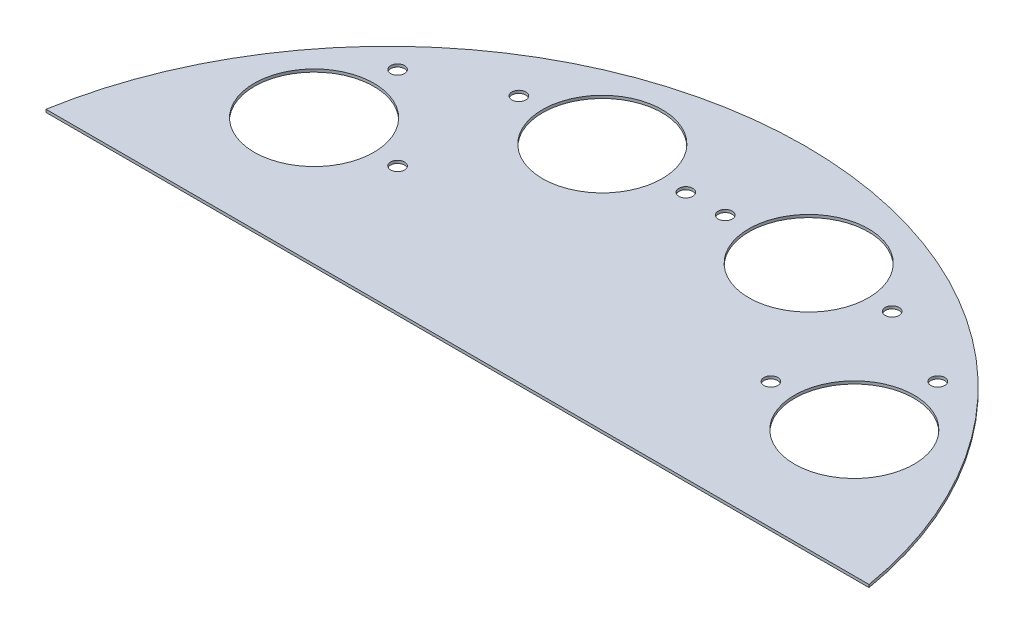
SolidWorks part; units mm, degrees
material "1060 Alloy"
ref_plane "Front Plane" through (0, 0, 0) normal (0, 0, 1) x (1, 0, 0)
ref_plane "Top Plane" through (0, 0, 0) normal (0, 1, 0) x (1, 0, 0)
ref_plane "Right Plane" through (0, 0, 0) normal (1, 0, 0) x (0, 0, -1)
sketch "Sketch3" plane through (0, 0, 0) normal (0, 1, 0) x (1, 0, 0)
  line L5 (-149.8445, -43.9726) -> (150.1555, -43.9726) construction
  line L6 (97.2375, 26.5616) -> (0.1555, -43.9726)
  line L7 (-86.3026, -18.9726) -> (-147.7465, -18.9726)
  line L9 (86.6136, -18.9726) -> (148.0575, -18.9726)
  line L11 (86.6136, -18.9726) -> (-86.3026, -18.9726)
  circle A10 centre (0.1555, -43.9726) radius 120 construction
  circle A11 centre (0.1555, -43.9726) radius 90 construction
  circle A12 centre (0.1555, -43.9726) radius 150
  circle A13 centre (97.2375, 26.5616) radius 21.5
  circle A14 centre (37.2375, 70.1542) radius 21.5
  circle A15 centre (-36.9265, 70.1542) radius 21.5
  circle A16 centre (-96.9265, 26.5616) radius 21.5
  point P5 (0.1555, -43.9726)
  point P9 (0.1555, -43.9726)
  point P22 (0.1555, -43.9726)
  dimension "D3" = 300
  dimension "D7" = 43
  dimension "D4" = 36
  dimension "D5" = 4
  dimension "D2" = 240
  dimension "D1" = 180
extrude "Boss-Extrude3" add sketch "Sketch3" along normal blind 1
sketch "Sketch5" plane through (0, 1, 0) normal (0, 1, 0) x (1, 0, 0)
  line L0 (37.2375, 70.1542) -> (-36.9265, 70.1542) construction
  line L1 (-36.9265, 70.1542) -> (-96.9265, 26.5616) construction
  line L2 (37.2375, 70.1542) -> (97.2375, 26.5616) construction
  circle A0 centre (97.2375, 26.5616) radius 30 construction
  circle A1 centre (37.2375, 70.1542) radius 30 construction
  circle A2 centre (-36.9265, 70.1542) radius 30 construction
  circle A3 centre (-96.9265, 26.5616) radius 30 construction
  point P12 (67.2375, 26.5616)
  point P13 (97.2375, 56.5616)
  point P14 (7.2375, 70.1542)
  point P15 (67.2375, 70.1542)
  point P16 (-6.9265, 70.1542)
  point P17 (-66.9265, 70.1542)
  point P18 (-96.9265, 56.5616)
  point P19 (-66.9265, 26.5616)
hole_wizard "Ø5.0mm Dowel Hole1" positions "Sketch8" profile "Sketch9" hole size "Ø5.0" standard "ANSI Metric" end condition through all
sketch "Sketch8" plane through (0, 0, 0) normal (0, -1, 0) x (-1, 0, 0)
  point P0 (-97.2375, 56.5616)
  point P2 (-67.2375, 26.5616)
  point P4 (-67.2375, 70.1542)
  point P6 (-7.2375, 70.1542)
  point P8 (6.9265, 70.1542)
  point P10 (66.9265, 70.1542)
  point P12 (96.9265, 56.5616)
  point P14 (66.9265, 26.5616)
sketch "Sketch9" plane through (97.2375, 0, -56.5616) normal (1, 0, 0) x (0, 0, -1)
  line L0 (0, 0) -> (0, 1)
  line L1 (0, 1) -> (2.5, 1)
  line L2 (2.5, 1) -> (2.5, 0)
  line L5 (2.5, 0) -> (0, 0)
  line L11 (0, -6.35) -> (0, 107.95) construction
  dimension "Thru Hole Dia." = 5
  dimension "Thru Hole Depth" = 1
